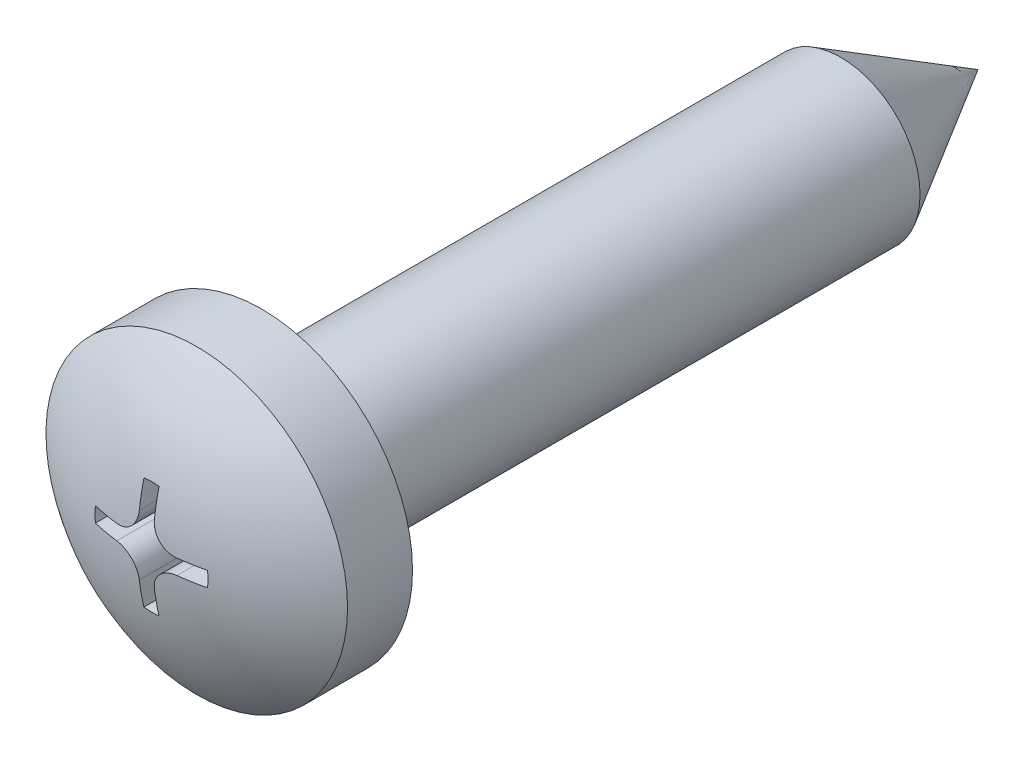
SolidWorks part; units mm, degrees
revolve "基体-旋转" add sketch "草图8" angle 360 about L0
sketch "草图8" plane through (0, 0, 0) normal (1, 0, 0) x (0, 0, -1)
  line L0 (-11.71, 0) -> (1.33, 0) construction
  line L1 (0, 0) -> (-22.1, 0)
  line L4 (-20.7235, 4) -> (-19, 4)
  line L5 (-19, 4) -> (-19, 2.1)
  line L6 (-19, 2.1) -> (-3.6373, 2.1)
  line L7 (-3.6373, 2.1) -> (0, 0)
  arc A0 (-22.1, 0) -> (-20.7235, 4) centre (-15.6, 0) cw
  dimension "D4" = 6.5
  dimension "D1" = 19
  dimension "D2" = 30
  dimension "D5" = 4.2
  dimension "D3" = 8
  dimension "D6" = 3.1
cosmetic thread "装饰螺纹线1" parameters "D1"=13.9, "D2"=3.6372
extrude "切除-拉伸2" cut sketch "草图7" against normal blind 1.8
sketch "草图7" plane through (0, 0, 22.1) normal (0, 0, 1) x (1, 0, 0)
  line L0 (-7.1, 0) -> (5.9, 0) construction
  line L1 (0, 7.5) -> (0, -7) construction
  line L2 (0.2, 1.4866) -> (0.2, 0.7975)
  line L3 (0, 0) -> (4.9858, 4.9858) construction
  line L4 (1.4866, 0.2) -> (0.7975, 0.2)
  line L5 (1.4866, -0.2) -> (0.7975, -0.2)
  line L6 (0.2, -1.4866) -> (0.2, -0.7975)
  line L7 (-0.2, -1.4866) -> (-0.2, -0.7975)
  line L8 (-1.4866, -0.2) -> (-0.7975, -0.2)
  line L9 (-1.4866, 0.2) -> (-0.7975, 0.2)
  line L10 (-0.2, 1.4866) -> (-0.2, 0.7975)
  line L11 (0, 0) -> (-4.9858, 4.9858) construction
  arc A0 (-0.2, 1.4866) -> (0.2, 1.4866) centre (0, 0) cw
  arc A1 (1.4866, -0.2) -> (1.4866, 0.2) centre (0, 0) ccw
  arc A2 (0.7975, 0.2) -> (0.2, 0.7975) centre (0.7975, 0.7975) cw
  arc A3 (-0.7975, 0.2) -> (-0.2, 0.7975) centre (-0.7975, 0.7975) ccw
  arc A4 (-0.2, -1.4866) -> (0.2, -1.4866) centre (0, 0) ccw
  arc A5 (0.7975, -0.2) -> (0.2, -0.7975) centre (0.7975, -0.7975) ccw
  arc A6 (-1.4866, -0.2) -> (-1.4866, 0.2) centre (0, 0) cw
  arc A7 (-0.7975, -0.2) -> (-0.2, -0.7975) centre (-0.7975, -0.7975) cw
  dimension "D10" = 1.5
  dimension "D1" = 0.5975
  dimension "D2" = 0.5975
material "冷镦钢"
ref_plane "前视" through (0, 0, 0) normal (0, 0, 1) x (1, 0, 0)
ref_plane "上视" through (0, 0, 0) normal (0, 1, 0) x (1, 0, 0)
ref_plane "右视" through (0, 0, 0) normal (1, 0, 0) x (0, 0, -1)
sketch "尺寸草图" plane through (0, 0, 0) normal (1, 0, 0) x (0, 0, -1)
  line L0 (-19, 8) -> (-19, 0)
  line L1 (-19, 0) -> (0, 0)
  line L2 (0, 0) -> (0, 4.2)
  point P4 (-15.9, 0)
  point P6 (0, 1.4)
  point P7 (-17.6, 0)
  point P8 (-19, 7.8)
  point P9 (-19, 1.5)
  point P10 (-3, 0)
  point P11 (-1.8, 0)
  point P12 (-18.38, 0)
  point P13 (-14.1, 0)
  point P14 (-15.3, 0)
  dimension "l" = 19
  dimension "E" = 8
  dimension "K" = 3.1
  dimension "d" = 4.2
  dimension "P" = 1.4
  dimension "A" = 1.4
  dimension "R" = 0.2
  dimension "Rf" = 6.5
  dimension "HM" = 3
  dimension "HH" = 1.8
  dimension "HE" = 0.62
  dimension "Da" = 4.9
  dimension "Yc" = 3.7
ref_plane "基准面6" through (0, 0, 22.1) normal (0, 0, 1) x (1, 0, 0)
sketch "草图9" plane through (0, 0, 0) normal (1, 0, 0) x (0, 0, -1)
  line L0 (-17.6, 2.1) -> (-16.2, 2.1)
  line L1 (-17.6, 2.1) -> (-17.075, 1.4)
  line L2 (-16.725, 1.4) -> (-17.075, 1.4)
  line L3 (-16.725, 1.4) -> (-16.2, 2.1)
  line L4 (-11.71, 0) -> (1.33, 0) construction
  line L5 (-19, -4) -> (-19, 4) construction
  line L6 (-6.912, 0) -> (-2.6011, 0) construction
  line L7 (-20.3, 0) -> (-21.9246, 0) construction
  dimension "D1" = 1.4
  dimension "D2" = 0.35
  dimension "D3" = 0.7
  dimension "D4" = 2.1
  dimension "D5" = 1.4
revolve "切除-旋转1" [suppressed] cut sketch "草图9" angle 360 about L6
pattern_linear "阵列(线性)1" [suppressed] count 10 spacing 1.75
fillet "圆角1" radius 0.2 1 edges at (2.1, 0, 19)
equation "\"D16@基准面6\" = \"l@尺寸草图\"+\"K@尺寸草图\""
equation "\"D1@草图8\" = \"l@尺寸草图\""
equation "\"D6@草图8\" = \"K@尺寸草图\""
equation "\"D5@草图8\" = \"d@尺寸草图\""
equation "\"D3@草图8\" = \"E@尺寸草图\""
equation "\"D4@草图8\" = \"Rf@尺寸草图\""
equation "\"D10@草图7\" = \"HM@尺寸草图\"/2"
equation "\"D1@切除-拉伸2\" = \"HH@尺寸草图\""
equation "\"D1@草图9\" = \"P@尺寸草图\""
equation "\"D2@草图9\" = \"D1@草图9\"/4"
equation "\"D3@草图9\" = \"D1@草图9\"/2"
equation "\"D4@草图9\" = \"d@尺寸草图\"/2"
equation "\"D5@草图9\" = \"A@尺寸草图\""
equation "\"D3@阵列(线性)1\" = \"A@尺寸草图\"*5/4"
equation "\"D1@阵列(线性)1\" = (\"l@尺寸草图\"-\"A@尺寸草图\")/\"D3@阵列(线性)1\""
equation "\"D2@装饰螺纹线1\" = \"d@尺寸草图\"*0.866"
equation "\"D1@装饰螺纹线1\" = \"l@尺寸草图\"-\"Yc@尺寸草图\"-\"A@尺寸草图\""
equation "\"D1@圆角1\" = \"R@尺寸草图\""
